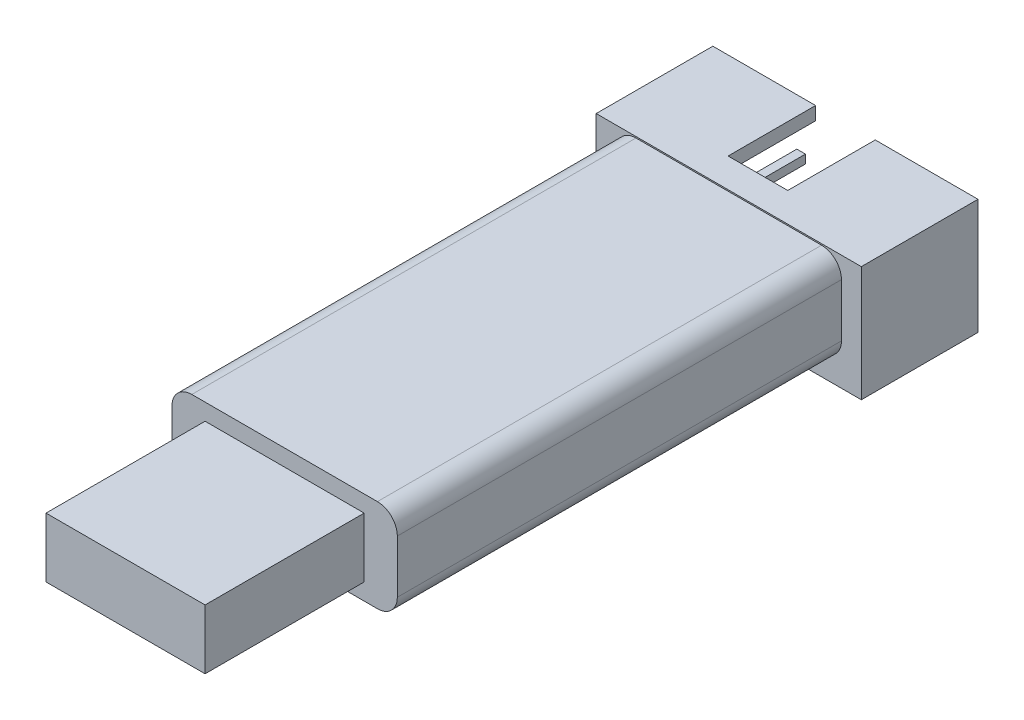
SolidWorks part; units mm, degrees
ref_plane "Front Plane" through (0, 0, 0) normal (0, 0, 1) x (1, 0, 0)
ref_plane "Top Plane" through (0, 0, 0) normal (0, 1, 0) x (1, 0, 0)
ref_plane "Right Plane" through (0, 0, 0) normal (1, 0, 0) x (0, 0, -1)
sketch "Sketch1" plane through (0, 0, 0) normal (0, 0, 1) x (1, 0, 0)
  line L1 (-6, -2.25) -> (6, -2.25)
  line L2 (-6, -2.25) -> (-6, 2.25)
  line L3 (-6, 2.25) -> (6, 2.25)
  line L4 (6, -2.25) -> (6, 2.25)
  line L5 (-6, -2.25) -> (6, 2.25) construction
  line L6 (-6, 2.25) -> (6, -2.25) construction
  point P0 (0, 0)
  dimension "D1" = 4.5
  dimension "D2" = 12
extrude "Boss-Extrude1" add sketch "Sketch1" against normal blind 12
sketch "Sketch2" plane through (0, 0, -12) normal (0, 0, -1) x (-1, 0, 0)
  line L1 (8.5, -3.5) -> (-8.5, -3.5)
  line L2 (8.5, -3.5) -> (8.5, 3.5)
  line L3 (8.5, 3.5) -> (-8.5, 3.5)
  line L4 (-8.5, -3.5) -> (-8.5, 3.5)
  line L5 (8.5, -3.5) -> (-8.5, 3.5) construction
  line L6 (8.5, 3.5) -> (-8.5, -3.5) construction
  point P0 (0, 0)
  dimension "D1" = 17
  dimension "D2" = 7
extrude "Boss-Extrude2" add sketch "Sketch2" along normal blind 33.5
sketch "Sketch3" plane through (0, 0, -45.5) normal (0, 0, -1) x (-1, 0, 0)
  line L0 (0, -0.75) -> (0, 0) construction
  line L1 (10, 3.6) -> (-10, 3.6)
  line L2 (10, 3.6) -> (10, -5.1)
  line L3 (10, -5.1) -> (-10, -5.1)
  line L4 (-10, 3.6) -> (-10, -5.1)
  line L5 (10, 3.6) -> (-10, -5.1) construction
  line L6 (10, -5.1) -> (-10, 3.6) construction
  line L8 (8.5, 3.5) -> (-8.5, 3.5) construction
  point P0 (0, -0.75)
  dimension "D1" = 20
  dimension "D2" = 8.7
  dimension "D3" = 0.1
extrude "Boss-Extrude3" add sketch "Sketch3" along normal blind 8.8
sketch "Sketch4" plane through (0, 0, -54.3) normal (0, 0, -1) x (-1, 0, 0)
  line L4 (-2.25, 2.6) -> (-2.25, 3.6)
  line L5 (10, 3.6) -> (-10, 3.6) construction
  line L6 (2.25, 2.6) -> (2.25, 3.6)
  line L7 (2.25, 3.1) -> (-2.25, 3.1) construction
  line L8 (-9, 2.6) -> (-9, -4.1)
  line L9 (-9, -4.1) -> (9, -4.1)
  line L10 (9, -4.1) -> (9, 2.6)
  line L11 (9, 2.6) -> (-9, 2.6)
  line L12 (-9, 2.6) -> (-9, -4.1)
  line L13 (-9, -4.1) -> (9, -4.1)
  line L14 (9, -4.1) -> (9, 2.6)
  line L15 (9, 2.6) -> (-9, 2.6)
  line L16 (0, 0) -> (0, 3.1) construction
  line M8 (10, 3.6) -> (-10, 3.6)
  dimension "D2" = 4.5
  dimension "D1" = 1
extrude "Cut-Extrude2" cut sketch "Sketch4" against normal blind 6.6 contours L14 L15 L12 L13 | L15 L6 L4 M8
sketch "Sketch5" plane through (0, 0, -47.7) normal (0, 0, -1) x (-1, 0, 0)
  line L0 (0, 0.52) -> (0, -2.02) construction
  line L1 (-0.325, 0.195) -> (0.325, 0.195)
  line L2 (-0.325, 0.195) -> (-0.325, 0.845)
  line L3 (-0.325, 0.845) -> (0.325, 0.845)
  line L4 (0.325, 0.195) -> (0.325, 0.845)
  line L5 (-0.325, 0.195) -> (0.325, 0.845) construction
  line L6 (-0.325, 0.845) -> (0.325, 0.195) construction
  line L7 (-0.325, -1.695) -> (0.325, -1.695)
  line L8 (-0.325, -1.695) -> (-0.325, -2.345)
  line L9 (-0.325, -2.345) -> (0.325, -2.345)
  line L10 (0.325, -1.695) -> (0.325, -2.345)
  line L11 (-0.325, -1.695) -> (0.325, -2.345) construction
  line L12 (-0.325, -2.345) -> (0.325, -1.695) construction
  line L13 (-9, -0.75) -> (0, -0.75) construction
  line L14 (-9, 2.6) -> (-9, -4.1) construction
  point P0 (0, 0.52)
  point P5 (0, -2.02)
  dimension "D1" = 0.65
  dimension "D2" = 2.54
extrude "Boss-Extrude4" add sketch "Sketch5" along normal blind 5.8
pattern_linear "LPattern1" count 3 spacing 2.54 along (1, 0, 0) count 3 spacing 2.54 along (-1, 0, 0) of "Boss-Extrude4"
fillet "Fillet1" radius 1.5 4 edges at (8.5, -3.5, -28.75) (8.5, 3.5, -28.75) (-8.5, -3.5, -28.75) (-8.5, 3.5, -28.75)
